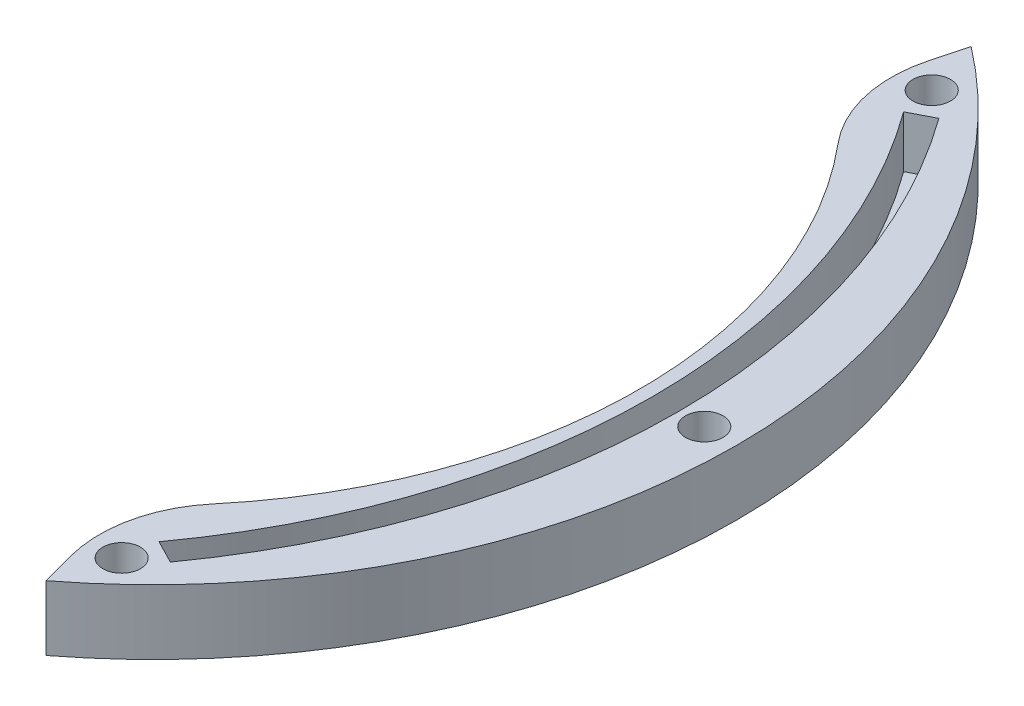
SolidWorks part; units mm, degrees
ref_plane "Спереди" through (0, 0, 0) normal (0, 0, 1) x (1, 0, 0)
ref_plane "Сверху" through (0, 0, 0) normal (0, 1, 0) x (1, 0, 0)
ref_plane "Справа" through (0, 0, 0) normal (1, 0, 0) x (0, 0, -1)
sketch "Эскиз1" plane through (0, 0, 0) normal (0, 1, 0) x (1, 0, 0)
  line L0 (25.2569, 27.7189) -> (27.3954, 35.7)
  line L1 (27.3954, -35.7) -> (25.2569, -27.7189)
  line L2 (-1000, 0) -> (49000, 0) construction
  arc A0 (27.3954, 35.7) -> (27.3954, -35.7) centre (0, 0) cw
  arc A1 (25.2569, 27.7189) -> (25.2569, -27.7189) centre (0, 0) cw
  point P1 (23.4846, 29.2356)
  dimension "D3" = 45
  dimension "D2" = 7.5
  dimension "D1" = 71.4
  dimension "D4" = 75
extrude "Бобышка-Вытянуть1" add sketch "Эскиз1" along normal blind 5
sketch "Эскиз2" plane through (0, 5, 0) normal (0, 1, 0) x (1, 0, 0)
  line L0 (-1000, 0) -> (49000, 0) construction
  line L1 (0, 0) -> (28.7938, 31.2596) construction
  line L2 (27.3954, 35.7) -> (25.2569, 27.7189) construction
  circle A0 centre (0, 0) radius 42.5 construction
  circle A1 centre (42.5, 0) radius 1.45
  circle A2 centre (28.7938, 31.2596) radius 1.45
  circle A4 centre (28.7938, -31.2596) radius 1.45
  dimension "D1" = 85
  dimension "D2" = 2.5
  dimension "D3" = 2.9
extrude "Вырез-Вытянуть1" cut sketch "Эскиз2" against normal blind 5
sketch "Эскиз3" plane through (0, 5, 0) normal (0, 1, 0) x (1, 0, 0)
  line L0 (29.1524, 28.7341) -> (30.9527, 29.6575)
  line L1 (29.1524, -28.7341) -> (30.9527, -29.6575)
  line L4 (40.5, -999.1092) -> (40.5, 49000.8908) construction
  line L5 (25.2569, -27.7189) -> (27.3954, -35.7) construction
  line L6 (-1000, 0) -> (49000, 0) construction
  arc A0 (29.1524, 28.7341) -> (29.1524, -28.7341) centre (-10.3375, 0) cw
  arc A1 (30.9527, -29.6575) -> (30.9527, 29.6575) centre (-10.3375, 0) ccw
  arc A2 (25.2569, -27.7189) -> (25.2569, 27.7189) centre (0, 0) ccw construction
  circle A6 centre (28.7938, -31.2596) radius 1.45 construction
  circle A7 centre (28.7938, -31.2596) radius 1.45 construction
  circle A8 centre (28.7938, 31.2596) radius 1.45 construction
  circle A9 centre (28.7938, 31.2596) radius 1.45 construction
  dimension "D1" = 2
  dimension "D2" = 1
  dimension "D3" = 40.5
  dimension "D4" = 5
  dimension "D5" = 3.5
  dimension "D6" = 7
extrude "Вырез-Вытянуть2" cut sketch "Эскиз3" against normal blind 4
fillet "Скругление1" radius 10 2 edges at (25.2569, 2.5, 27.7189) (25.2569, 2.5, -27.7189)
